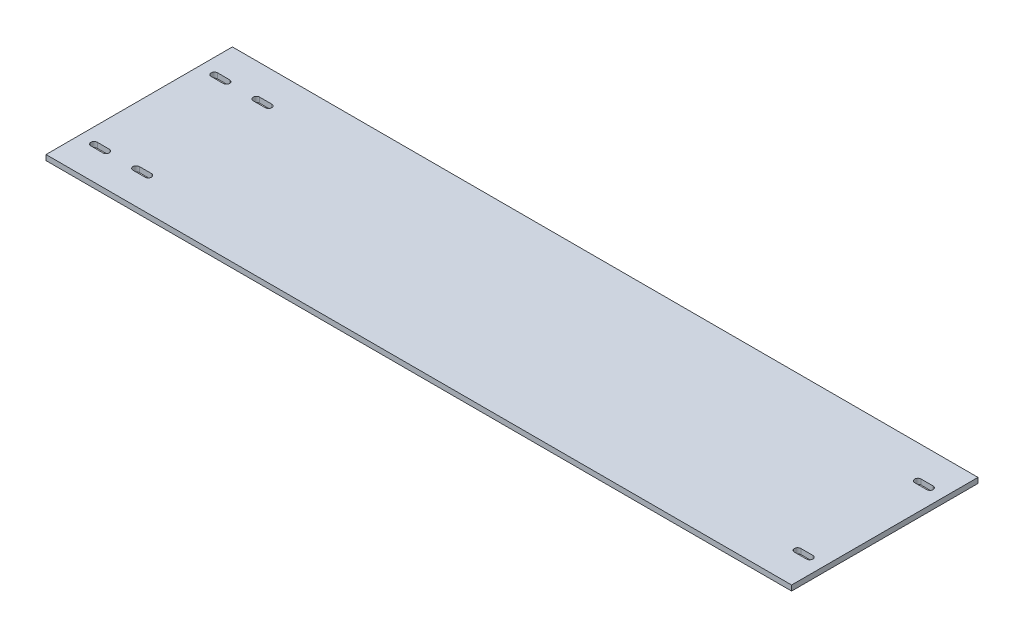
SolidWorks part; units mm, degrees
material "PC High Viscosity"
ref_plane "Front" through (0, 0, 0) normal (0, 0, 1) x (1, 0, 0)
ref_plane "Top" through (0, 0, 0) normal (0, 1, 0) x (1, 0, 0)
ref_plane "Right" through (0, 0, 0) normal (1, 0, 0) x (0, 0, -1)
sketch "Sketch1" plane through (0, 0, 0) normal (0, 1, 0) x (1, 0, 0)
  line L0 (15.875, 34.925) -> (28.575, 34.925) construction
  line L1 (0, 0) -> (787.4, 0)
  line L2 (0, 0) -> (0, 196.85)
  line L3 (0, 196.85) -> (787.4, 196.85)
  line L4 (787.4, 0) -> (787.4, 196.85)
  line L5 (15.875, 38.3032) -> (28.575, 38.3032)
  line L6 (15.875, 31.5468) -> (28.575, 31.5468)
  line L7 (22.225, 34.925) -> (22.225, 161.925) construction
  line L8 (15.875, 161.925) -> (28.575, 161.925) construction
  line L9 (15.875, 165.3032) -> (28.575, 165.3032)
  line L10 (15.875, 158.5468) -> (28.575, 158.5468)
  line L11 (22.225, 161.925) -> (66.675, 161.925) construction
  line L12 (66.675, 161.925) -> (66.675, 34.925) construction
  line L13 (66.675, 34.925) -> (22.225, 34.925) construction
  line L14 (60.325, 161.925) -> (73.025, 161.925) construction
  line L15 (60.325, 165.3032) -> (73.025, 165.3032)
  line L16 (60.325, 158.5468) -> (73.025, 158.5468)
  line L17 (60.325, 34.925) -> (73.025, 34.925) construction
  line L18 (60.325, 38.3032) -> (73.025, 38.3032)
  line L19 (60.325, 31.5468) -> (73.025, 31.5468)
  line L20 (765.175, 161.925) -> (765.175, 34.925) construction
  line L21 (771.525, 161.925) -> (758.825, 161.925) construction
  line L22 (771.525, 158.5468) -> (758.825, 158.5468)
  line L23 (771.525, 165.3032) -> (758.825, 165.3032)
  line L24 (771.525, 34.925) -> (758.825, 34.925) construction
  line L25 (771.525, 31.5468) -> (758.825, 31.5468)
  line L26 (771.525, 38.3032) -> (758.825, 38.3032)
  arc A0 (15.875, 38.3032) -> (15.875, 31.5468) centre (15.875, 34.925) ccw
  arc A1 (28.575, 31.5468) -> (28.575, 38.3032) centre (28.575, 34.925) ccw
  arc A2 (15.875, 165.3032) -> (15.875, 158.5468) centre (15.875, 161.925) ccw
  arc A3 (28.575, 158.5468) -> (28.575, 165.3032) centre (28.575, 161.925) ccw
  arc A4 (60.325, 165.3032) -> (60.325, 158.5468) centre (60.325, 161.925) ccw
  arc A5 (73.025, 158.5468) -> (73.025, 165.3032) centre (73.025, 161.925) ccw
  arc A6 (60.325, 38.3032) -> (60.325, 31.5468) centre (60.325, 34.925) ccw
  arc A7 (73.025, 31.5468) -> (73.025, 38.3032) centre (73.025, 34.925) ccw
  arc A8 (771.525, 158.5468) -> (771.525, 165.3032) centre (771.525, 161.925) ccw
  arc A9 (758.825, 165.3032) -> (758.825, 158.5468) centre (758.825, 161.925) ccw
  arc A10 (771.525, 31.5468) -> (771.525, 38.3032) centre (771.525, 34.925) ccw
  arc A11 (758.825, 38.3032) -> (758.825, 31.5468) centre (758.825, 34.925) ccw
  point P7 (22.225, 34.925)
  point P13 (22.225, 161.925)
  point P25 (66.675, 161.925)
  point P31 (66.675, 34.925)
  point P40 (765.175, 161.925)
  point P47 (765.175, 34.925)
  dimension "D1" = 6.7564
  dimension "D2" = 34.925
  dimension "D3" = 12.7
  dimension "D4" = 22.225
  dimension "D5" = 127
  dimension "D6" = 34.925
  dimension "D7" = 44.45
  dimension "D8" = 22.225
  dimension "D9" = 698.5
extrude "Boss-Extrude1" add sketch "Sketch1" along normal blind 5.588
fillet "Fillet1" [suppressed] radius 3.175
sketch "Sketch2" plane through (0, 5.588, 0) normal (0, 1, 0) x (1, 0, 0)
  line L0 (0, 98.425) -> (787.4, 98.425) construction
  line L1 (0, 196.85) -> (0, 0) construction
  line L2 (787.4, 0) -> (787.4, 196.85) construction
  line L3 (787.4, 196.85) -> (0, 196.85) construction
  line L4 (133.35, 25.4) -> (698.5, 25.4) construction
  line L5 (133.35, 25.4) -> (133.35, 171.45) construction
  line L6 (133.35, 171.45) -> (698.5, 171.45) construction
  line L7 (698.5, 25.4) -> (698.5, 171.45) construction
  line L8 (133.35, 25.4) -> (698.5, 171.45) construction
  line L9 (133.35, 171.45) -> (698.5, 25.4) construction
  line L10 (73.025, 161.925) -> (133.35, 161.925) construction
  line L11 (758.825, 161.925) -> (698.5, 161.925) construction
  circle A0 centre (133.35, 171.45) radius 3.3782
  circle A1 centre (133.35, 25.4) radius 3.3782
  circle A2 centre (698.5, 25.4) radius 3.3782
  circle A3 centre (698.5, 171.45) radius 3.3782
  point P6 (415.925, 98.425)
  dimension "D2" = 6.7564
  dimension "D1" = 88.9
  dimension "D3" = 25.4
extrude "Cut-Extrude1" [suppressed] cut sketch "Sketch2" against normal through all
